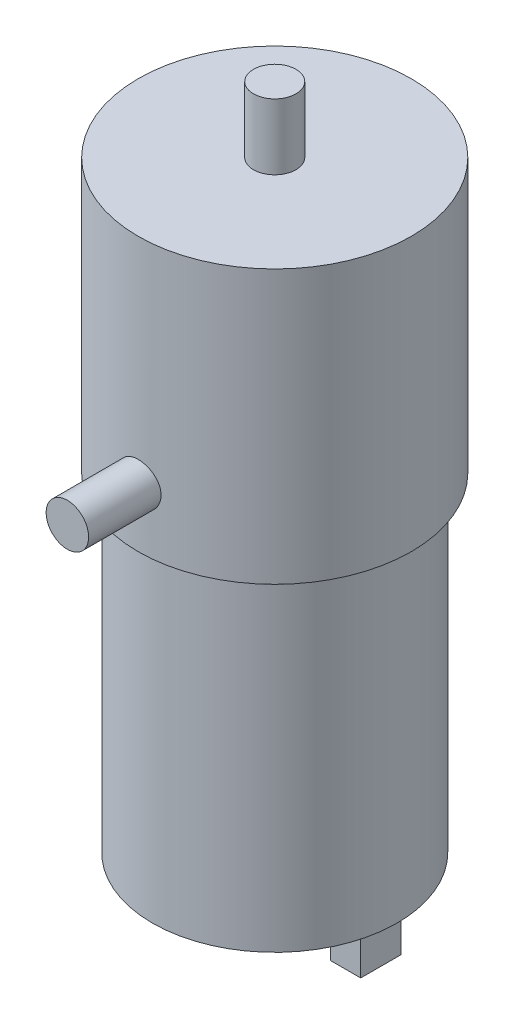
SolidWorks part; units mm, degrees
ref_plane "Plan de face" through (0, 0, 0) normal (0, 0, 1) x (1, 0, 0)
ref_plane "Plan de dessus" through (0, 0, 0) normal (0, 1, 0) x (1, 0, 0)
ref_plane "Plan de droite" through (0, 0, 0) normal (1, 0, 0) x (0, 0, -1)
sketch "Esquisse1" plane through (0, 0, 0) normal (0, 0, 1) x (1, 0, 0)
  line L0 (0, 44.1715) -> (0, -58.4059) construction
  line L1 (0, 33.5) -> (0, -32.5)
  line L2 (0, -32.5) -> (12.1, -32.5)
  line L3 (12.1, -32.5) -> (12.1, -1)
  line L4 (11.1, 0) -> (13.5, 0)
  line L5 (13.5, 0) -> (13.5, 27)
  line L6 (13.5, 27) -> (2.1, 27)
  line L7 (2.1, 27) -> (2.1, 33.5)
  line L8 (2.1, 33.5) -> (0, 33.5)
  arc A0 (12.1, -1) -> (11.1, 0) centre (11.1, -1) ccw
  dimension "D7" = 1
  dimension "D1" = 27
  dimension "D2" = 59.5
  dimension "D3" = 6.5
  dimension "D4" = 4.2
  dimension "D5" = 27
  dimension "D6" = 24.2
revolve "Révolution1" add sketch "Esquisse1" angle 360 about L0
sketch "Esquisse2" plane through (0, 0, 0) normal (0, 0, 1) x (1, 0, 0)
  line L0 (13.5, 27) -> (-13.5, 27) construction
  circle A0 centre (0, 5.8) radius 2.1
  dimension "D1" = 4.2
  dimension "D2" = 21.2
extrude "Boss.-Extru.1" add sketch "Esquisse2" along normal blind 20.5
sketch "Esquisse3" plane through (0, -32.5, 0) normal (0, -1, 0) x (1, 0, 0)
  line L0 (-7.5, 0) -> (7.5, 0) construction
  line L1 (-10.5, 2) -> (-7.5, 2)
  line L2 (-10.5, 2) -> (-10.5, -2)
  line L3 (-10.5, -2) -> (-7.5, -2)
  line L4 (-7.5, 2) -> (-7.5, -2)
  line L5 (7.5, 2) -> (10.5, 2)
  line L6 (7.5, 2) -> (7.5, -2)
  line L7 (7.5, -2) -> (10.5, -2)
  line L8 (10.5, 2) -> (10.5, -2)
  dimension "D1" = 15
  dimension "D2" = 21
  dimension "D3" = 4
extrude "Boss.-Extru.2" add sketch "Esquisse3" along normal blind 4.5
ref_point "Point1"
